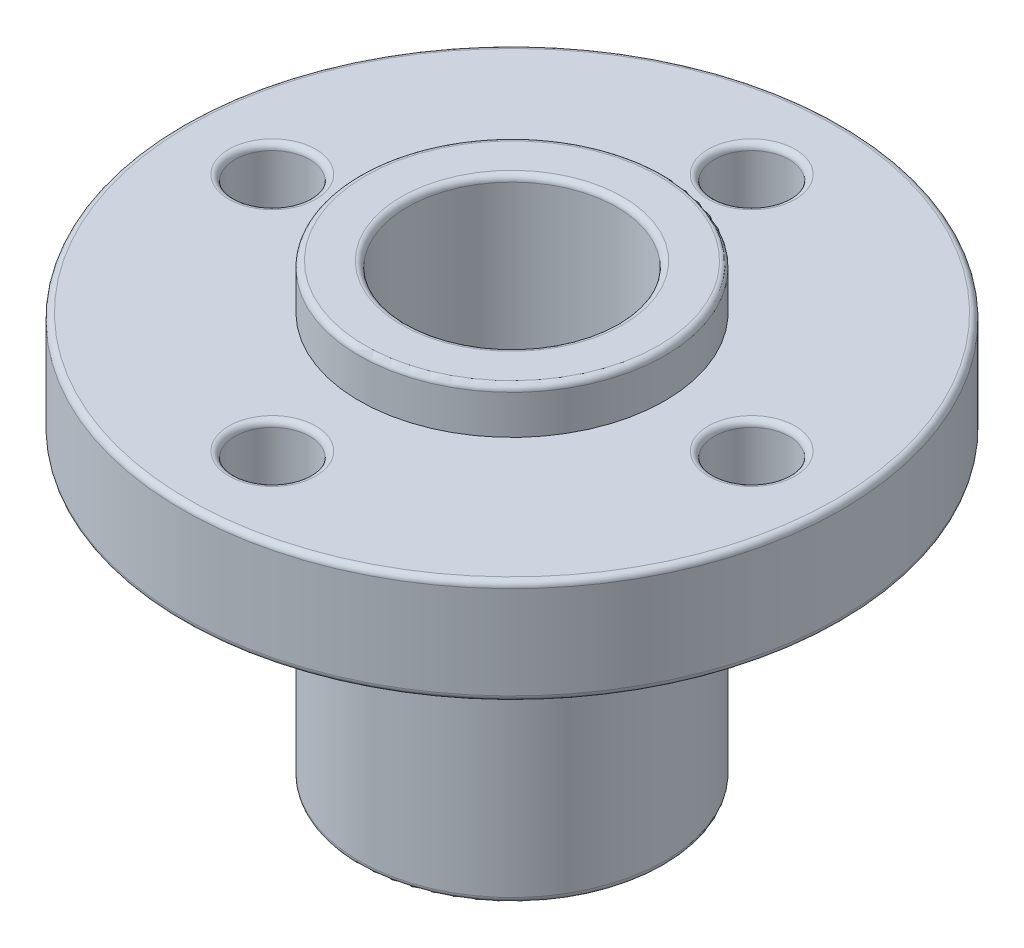
SolidWorks part; units mm, degrees
material "Brass"
ref_plane "Front Plane" through (0, 0, 0) normal (0, 0, 1) x (1, 0, 0)
ref_plane "Top Plane" through (0, 0, 0) normal (0, 1, 0) x (1, 0, 0)
ref_plane "Right Plane" through (0, 0, 0) normal (1, 0, 0) x (0, 0, -1)
sketch "Sketch1" plane through (0, 0, 0) normal (0, 0, 1) x (1, 0, 0)
  line L0 (-213.9291, 0) -> (10482.5275, 0) construction
  line L1 (0, -213.9291) -> (0, 10482.5275) construction
  line L2 (3.7, 3.25) -> (4.9, 3.25)
  line L3 (5.1, 3.05) -> (5.1, 1.75)
  line L4 (5.1, 1.75) -> (10.8, 1.75)
  line L5 (11, 1.55) -> (11, -1.55)
  line L6 (10.8, -1.75) -> (5.1, -1.75)
  line L7 (5.1, -1.75) -> (5.1, -11.55)
  line L8 (4.9, -11.75) -> (3.7, -11.75)
  line L9 (3.5, -11.55) -> (3.5, 3.05)
  arc A0 (5.1, -11.55) -> (4.9, -11.75) centre (4.9, -11.55) cw
  arc A1 (11, -1.55) -> (10.8, -1.75) centre (10.8, -1.55) cw
  arc A2 (10.8, 1.75) -> (11, 1.55) centre (10.8, 1.55) cw
  arc A3 (4.9, 3.25) -> (5.1, 3.05) centre (4.9, 3.05) cw
  arc A4 (3.7, 3.25) -> (3.5, 3.05) centre (3.7, 3.05) ccw
  arc A5 (3.7, -11.75) -> (3.5, -11.55) centre (3.7, -11.55) cw
  point P7 (11, 0)
  dimension "D8" = 0.2
  dimension "D9" = 0.2
  dimension "D1" = 5.1
  dimension "D2" = 10
  dimension "D3" = 3.5
  dimension "D4" = 3.5
  dimension "D5" = 11
  dimension "D6" = 1.5
  dimension "D7" = 1.75
revolve "Revolve1" add sketch "Sketch1" angle 360 about L1
sketch "Sketch2" plane through (0, 1.75, 0) normal (0, 1, 0) x (1, 0, 0)
  line L0 (0, -1000) -> (0, 49000) construction
  line L1 (-1000, 0) -> (49000, 0) construction
  circle A0 centre (8, 0) radius 1.25
  circle A1 centre (0, 0) radius 10.8
  circle A2 centre (0, 0) radius 10.8 construction
  circle A3 centre (0, -8) radius 1.25
  circle A4 centre (-8, 0) radius 1.25
  circle A5 centre (0, 8) radius 1.25
  dimension "D2" = 2.5
  dimension "D3" = 8
  dimension "D1" = 0
  dimension "D4" = 4
extrude "Cut-Extrude1" cut sketch "Sketch2" against normal up to next
fillet "Fillet1" radius 0.2 8 edges at (-6.75, -1.75, 0) (1.25, -1.75, 8) (9.25, -1.75, 0) (1.25, -1.75, -8) (-9.25, 1.75, 0) (-1.25, 1.75, 8) (6.75, 1.75, 0) (-1.25, 1.75, -8)
